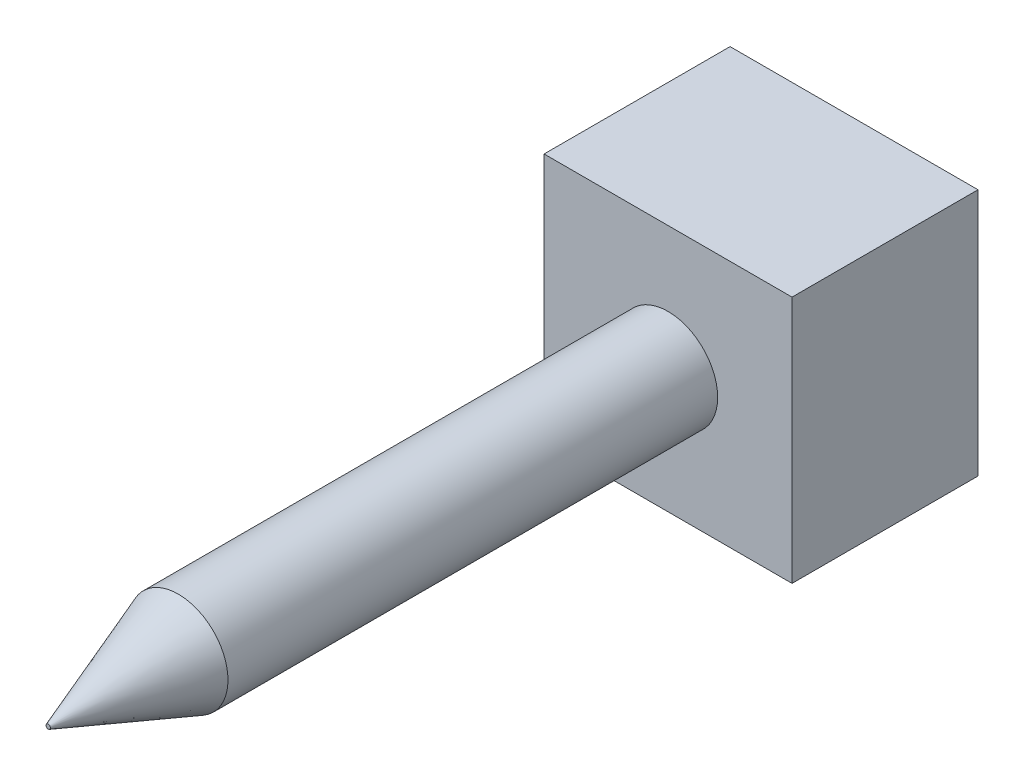
SolidWorks part; units mm, degrees
ref_plane "Front Plane" through (0, 0, 0) normal (0, 0, 1) x (1, 0, 0)
ref_plane "Top Plane" through (0, 0, 0) normal (0, 1, 0) x (1, 0, 0)
ref_plane "Right Plane" through (0, 0, 0) normal (1, 0, 0) x (0, 0, -1)
sketch "Sketch1" plane through (0, 0, 0) normal (0, 0, 1) x (1, 0, 0)
  line L1 (-10, 10) -> (10, 10)
  line L2 (-10, 10) -> (-10, -10)
  line L3 (-10, -10) -> (10, -10)
  line L4 (10, 10) -> (10, -10)
  line L5 (-10, 10) -> (10, -10) construction
  line L6 (-10, -10) -> (10, 10) construction
  point P0 (0, 0)
  dimension "D1" = 20
extrude "Boss-Extrude1" add sketch "Sketch1" along normal blind 15
sketch "Sketch2" plane through (0, 0, 15) normal (0, 0, 1) x (1, 0, 0)
  circle A0 centre (0, 0) radius 4
  dimension "D1" = 8
extrude "Boss-Extrude2" add sketch "Sketch2" along normal blind 50
chamfer "Chamfer1" distance 10.5 angle 20 1 edges at (4, 0, 65)
